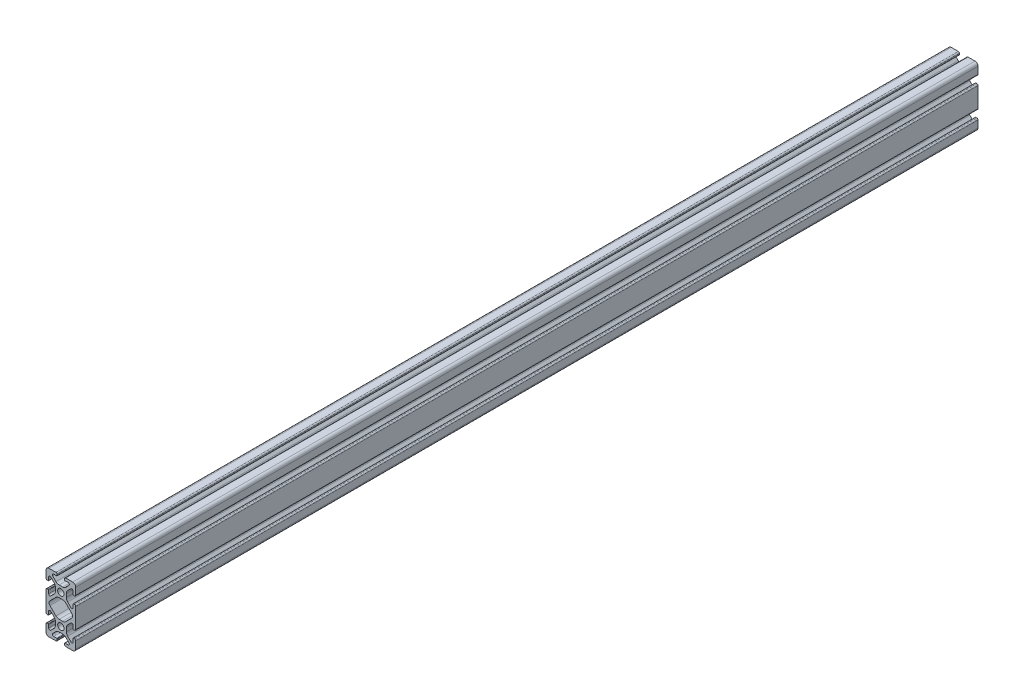
SolidWorks part; units mm, degrees
ref_plane "Front Plane" through (0, 0, 0) normal (0, 0, 1) x (1, 0, 0)
ref_plane "Top Plane" through (0, 0, 0) normal (0, 1, 0) x (1, 0, 0)
ref_plane "Right Plane" through (0, 0, 0) normal (1, 0, 0) x (0, 0, -1)
sketch "Sketch1" plane through (0, 0, 0) normal (0, 0, 1) x (1, 0, 0)
  line L0 (0, 10) -> (0, 20) construction
  line L1 (0, 10) -> (10, 10) construction
  line L2 (0, 10) -> (-10, 20) construction
  line L3 (-8, 20) -> (-3.3, 20)
  line L4 (-10, 20) -> (0, 20) construction
  line L6 (-2.8, 18.2) -> (-4.9051, 18.2)
  line L10 (0, 13.7) -> (-1.2022, 13.7)
  line L11 (-3.3236, 14.5787) -> (-5.5025, 16.7576)
  line L24 (0, 10) -> (-10, 10) construction
  line L25 (-10, 10) -> (0, 10) construction
  line L27 (-10, 0) -> (-10, 20) construction
  line L28 (0, 20) -> (10, 20) construction
  line L29 (-2.5, 18.5) -> (-2.5, 19.2)
  line L30 (-10, -20) -> (10, -20) construction
  line L31 (0, 20) -> (0, -20) construction
  arc A0 (-9.4142, 19.4142) -> (-8, 20) centre (-8, 18) cw
  arc A5 (-3.3, 20) -> (-2.5, 19.2) centre (-3.3, 19.2) cw
  arc A6 (-1.2022, 13.7) -> (-3.3236, 14.5787) centre (-1.2022, 16.7) cw
  circle A16 centre (0, 10) radius 2.15
  arc A18 (-5.5025, 16.7576) -> (-4.9051, 18.2) centre (-4.9051, 17.3551) cw
  arc A20 (-2.8, 18.2) -> (-2.5, 18.5) centre (-2.8, 18.5) ccw
  point P15 (0, -20)
  point P24 (0, 0)
  point P42 (-2.4449, 13.7)
  point P80 (-10, 10)
  dimension "D11" = 2
  dimension "D15" = 3
  dimension "Center Hole Diameter" = 4.3
  dimension "D7" = 0.8
  dimension "D8" = 0.3
  dimension "D4" = 0.8449
  dimension "D1" = 45
  dimension "Rail Width" = 20
  dimension "T-Slot Depth" = 6.3
  dimension "D9" = 1.8
  dimension "D23" = 7.4
  dimension "D5" = 11.5
  dimension "T-Slot Width" = 5
  dimension "D3" = 1.775
  dimension "D6" = 9.8102
  dimension "Rail Height" = 40
sketch "Sketch2" plane through (0, 0, 0) normal (1, 0, 0) x (0, 0, -1)
  line L0 (-304.8, 0) -> (304.8, 0)
  line L1 (-304.8, -20) -> (-304.8, 20)
  line L2 (0, 10) -> (0, 20) construction
  line L3 (0, 0) -> (0, 20) construction
  line L4 (304.8, -20) -> (304.8, 20)
  line L5 (-10, 10) -> (10, 10) construction
  point P0 (-279.8, 0)
  point P3 (0, 0)
  point P7 (279.8, 0)
  point P11 (-304.8, 0)
  point P14 (304.8, 0)
  point P23 (0, 10)
  dimension "D1" = 25
  dimension "Length" = 609.6
sketch "Sketch3" plane through (0, 0, 0) normal (0, 0, 1) x (1, 0, 0)
  line L0 (-2.5, 18.5) -> (-2.5, 19.2) construction
  line L1 (0, 10) -> (-10, 20) construction
  line L2 (0, 10) -> (-10, 20) construction
  line L5 (-8, 20) -> (-3.3, 20) construction
  line L6 (-2.8, 18.2) -> (-4.9051, 18.2) construction
  line L7 (-8.5, 7.5) -> (-9.2, 7.5)
  line L17 (-2.5, 18.5) -> (-2.5, 19.2)
  line L19 (-2.8, 18.2) -> (-4.9051, 18.2)
  line L21 (-3.7, 10) -> (0, 10) construction
  line L22 (-3.7, 8.7978) -> (-3.7, 11.2022)
  line L23 (-4.5787, 13.3236) -> (-6.7576, 15.5025)
  line L42 (-3.3236, 14.5787) -> (-5.5025, 16.7576) construction
  line L43 (0, 13.7) -> (-1.2022, 13.7) construction
  line L44 (-8, 20) -> (-3.3, 20)
  line L47 (-3.3236, 14.5787) -> (-5.5025, 16.7576)
  line L48 (1.2022, 13.7) -> (-1.2022, 13.7)
  line L59 (0, 13.7) -> (0, 12.15) construction
  line L60 (-10, 18) -> (-10, 13.3)
  line L61 (-8.2, 12.8) -> (-8.2, 14.9051)
  line L62 (-8.5, 12.5) -> (-9.2, 12.5)
  line L63 (-8.2, 7.2) -> (-8.2, 5.0949)
  line L64 (-10, 0) -> (-10, 6.7)
  line L65 (1.2022, 6.3) -> (-1.2022, 6.3)
  line L66 (-3.3236, 5.4213) -> (-7.3307, 1.4142)
  line L68 (-4.5787, 6.6764) -> (-6.7576, 4.4975)
  line L73 (10, 0) -> (-10, 0) construction
  line L78 (4.5787, 6.6764) -> (6.7576, 4.4975)
  line L79 (3.3236, 5.4213) -> (7.3307, 1.4142)
  line L81 (10, 0) -> (10, 6.7)
  line L82 (8.2, 7.2) -> (8.2, 5.0949)
  line L83 (8.5, 12.5) -> (9.2, 12.5)
  line L84 (8.2, 12.8) -> (8.2, 14.9051)
  line L85 (10, 18) -> (10, 13.3)
  line L87 (3.3236, 14.5787) -> (5.5025, 16.7576)
  line L88 (8, 20) -> (3.3, 20)
  line L89 (4.5787, 13.3236) -> (6.7576, 15.5025)
  line L90 (3.7, 8.7978) -> (3.7, 11.2022)
  line L91 (2.8, 18.2) -> (4.9051, 18.2)
  line L92 (2.5, 18.5) -> (2.5, 19.2)
  line L93 (8.5, 7.5) -> (9.2, 7.5)
  line L94 (-10, 0) -> (-7.9165, 0)
  line L96 (7.9165, 0) -> (10, 0)
  arc A0 (-8, 20) -> (-9.4142, 19.4142) centre (-8, 18) ccw construction
  arc A1 (-2.8, 18.2) -> (-2.5, 18.5) centre (-2.8, 18.5) ccw construction
  arc A3 (-2.8, 18.2) -> (-2.5, 18.5) centre (-2.8, 18.5) ccw
  arc A5 (-8, 20) -> (-10, 18) centre (-8, 18) ccw
  arc A10 (-3.3236, 5.4213) -> (-1.2022, 6.3) centre (-1.2022, 3.3) cw
  circle A13 centre (0, 10) radius 2.15 construction
  circle A14 centre (0, 10) radius 2.15
  arc A15 (-4.5787, 13.3236) -> (-3.7, 11.2022) centre (-6.7, 11.2022) cw
  arc A16 (-8.2, 14.9051) -> (-6.7576, 15.5025) centre (-7.3551, 14.9051) cw
  arc A17 (-9.2, 12.5) -> (-10, 13.3) centre (-9.2, 13.3) cw
  arc A18 (-8.2, 12.8) -> (-8.5, 12.5) centre (-8.5, 12.8) cw
  arc A36 (-2.5, 19.2) -> (-3.3, 20) centre (-3.3, 19.2) ccw construction
  arc A38 (-4.9051, 18.2) -> (-5.5025, 16.7576) centre (-4.9051, 17.3551) ccw construction
  arc A39 (-3.3236, 14.5787) -> (-1.2022, 13.7) centre (-1.2022, 16.7) ccw construction
  arc A41 (-2.5, 19.2) -> (-3.3, 20) centre (-3.3, 19.2) ccw
  arc A43 (-4.9051, 18.2) -> (-5.5025, 16.7576) centre (-4.9051, 17.3551) ccw
  arc A44 (-3.3236, 14.5787) -> (-1.2022, 13.7) centre (-1.2022, 16.7) ccw
  arc A47 (-8.2, 7.2) -> (-8.5, 7.5) centre (-8.5, 7.2) ccw
  arc A48 (-9.2, 7.5) -> (-10, 6.7) centre (-9.2, 6.7) ccw
  arc A49 (-8.2, 5.0949) -> (-6.7576, 4.4975) centre (-7.3551, 5.0949) ccw
  arc A50 (-4.5787, 6.6764) -> (-3.7, 8.7978) centre (-6.7, 8.7978) ccw
  arc A54 (-7.9165, 0) -> (-7.3307, 1.4142) centre (-5.9165, 0) cw
  arc A57 (7.9165, 0) -> (7.3307, 1.4142) centre (5.9165, 0) ccw
  arc A58 (4.5787, 6.6764) -> (3.7, 8.7978) centre (6.7, 8.7978) cw
  arc A59 (8.2, 5.0949) -> (6.7576, 4.4975) centre (7.3551, 5.0949) cw
  arc A60 (9.2, 7.5) -> (10, 6.7) centre (9.2, 6.7) cw
  arc A61 (8.2, 7.2) -> (8.5, 7.5) centre (8.5, 7.2) cw
  arc A62 (3.3236, 14.5787) -> (1.2022, 13.7) centre (1.2022, 16.7) cw
  arc A63 (4.9051, 18.2) -> (5.5025, 16.7576) centre (4.9051, 17.3551) cw
  arc A64 (2.5, 19.2) -> (3.3, 20) centre (3.3, 19.2) cw
  arc A65 (8.2, 12.8) -> (8.5, 12.5) centre (8.5, 12.8) ccw
  arc A66 (9.2, 12.5) -> (10, 13.3) centre (9.2, 13.3) ccw
  arc A67 (8.2, 14.9051) -> (6.7576, 15.5025) centre (7.3551, 14.9051) ccw
  arc A68 (4.5787, 13.3236) -> (3.7, 11.2022) centre (6.7, 11.2022) ccw
  arc A70 (3.3236, 5.4213) -> (1.2022, 6.3) centre (1.2022, 3.3) ccw
  arc A71 (8, 20) -> (10, 18) centre (8, 18) cw
  arc A72 (2.8, 18.2) -> (2.5, 18.5) centre (2.8, 18.5) cw
  point P59 (-10, 2)
  point P71 (0, 0)
  point P116 (0, 6.3)
extrude "Boss-Extrude1" add sketch "Sketch3" along normal mid plane 609.6
pattern_circular "CirPattern1" count 2 over 360 about axis through (0, 0, 0) along (0, 0, 1) of "Boss-Extrude1"
sketch "Sketch4" plane through (0, 0, 304.8) normal (0, 0, 1) x (1, 0, 0)
  line L0 (7.3307, -1.4142) -> (3.3236, -5.4213) construction
  line L1 (-3.3236, -5.4213) -> (-7.3307, -1.4142) construction
  line L2 (1.2022, -6.3) -> (-1.2022, -6.3) construction
  line L3 (3.3236, 5.4213) -> (7.3307, 1.4142) construction
  line L4 (-1.2022, 6.3) -> (1.2022, 6.3) construction
  line L5 (-7.3307, 1.4142) -> (-3.3236, 5.4213) construction
  line L6 (7.3307, -1.4142) -> (3.3236, -5.4213)
  line L7 (-3.3236, -5.4213) -> (-7.3307, -1.4142)
  line L8 (1.2022, -6.3) -> (-1.2022, -6.3)
  line L9 (3.3236, 5.4213) -> (7.3307, 1.4142)
  line L10 (-1.2022, 6.3) -> (1.2022, 6.3)
  line L11 (-7.3307, 1.4142) -> (-3.3236, 5.4213)
  line L52 (-2.5, 18.5) -> (-2.5, 19.2)
  line L53 (-3.3, 20) -> (-8, 20)
  line L54 (-10, 18) -> (-10, 13.3)
  line L55 (-9.2, 12.5) -> (-8.5, 12.5)
  line L56 (-8.2, 12.8) -> (-8.2, 14.9051)
  line L57 (-6.7576, 15.5025) -> (-4.5787, 13.3236)
  line L58 (-3.7, 11.2022) -> (-3.7, 8.7978)
  line L59 (-4.5787, 6.6764) -> (-6.7576, 4.4975)
  line L60 (-8.2, 5.0949) -> (-8.2, 7.2)
  line L61 (-8.5, 7.5) -> (-9.2, 7.5)
  line L62 (-10, 6.7) -> (-10, -6.7)
  line L63 (-9.2, -7.5) -> (-8.5, -7.5)
  line L64 (-8.2, -7.2) -> (-8.2, -5.0949)
  line L65 (-6.7576, -4.4975) -> (-4.5787, -6.6764)
  line L66 (-3.7, -8.7978) -> (-3.7, -11.2022)
  line L67 (-4.5787, -13.3236) -> (-6.7576, -15.5025)
  line L68 (-8.2, -14.9051) -> (-8.2, -12.8)
  line L69 (-8.5, -12.5) -> (-9.2, -12.5)
  line L70 (-10, -13.3) -> (-10, -18)
  line L71 (-8, -20) -> (-3.3, -20)
  line L72 (-2.5, -19.2) -> (-2.5, -18.5)
  line L73 (-2.8, -18.2) -> (-4.9051, -18.2)
  line L74 (-5.5025, -16.7576) -> (-3.3236, -14.5787)
  line L75 (-1.2022, -13.7) -> (1.2022, -13.7)
  line L76 (3.3236, -14.5787) -> (5.5025, -16.7576)
  line L77 (4.9051, -18.2) -> (2.8, -18.2)
  line L78 (2.5, -18.5) -> (2.5, -19.2)
  line L79 (3.3, -20) -> (8, -20)
  line L80 (10, -18) -> (10, -13.3)
  line L81 (9.2, -12.5) -> (8.5, -12.5)
  line L82 (8.2, -12.8) -> (8.2, -14.9051)
  line L83 (6.7576, -15.5025) -> (4.5787, -13.3236)
  line L84 (3.7, -11.2022) -> (3.7, -8.7978)
  line L85 (4.5787, -6.6764) -> (6.7576, -4.4975)
  line L86 (8.2, -5.0949) -> (8.2, -7.2)
  line L87 (8.5, -7.5) -> (9.2, -7.5)
  line L88 (10, -6.7) -> (10, 6.7)
  line L89 (9.2, 7.5) -> (8.5, 7.5)
  line L90 (8.2, 7.2) -> (8.2, 5.0949)
  line L91 (6.7576, 4.4975) -> (4.5787, 6.6764)
  line L92 (3.7, 8.7978) -> (3.7, 11.2022)
  line L93 (4.5787, 13.3236) -> (6.7576, 15.5025)
  line L94 (8.2, 14.9051) -> (8.2, 12.8)
  line L95 (8.5, 12.5) -> (9.2, 12.5)
  line L96 (10, 13.3) -> (10, 18)
  line L97 (8, 20) -> (3.3, 20)
  line L98 (2.5, 19.2) -> (2.5, 18.5)
  line L99 (2.8, 18.2) -> (4.9051, 18.2)
  line L100 (5.5025, 16.7576) -> (3.3236, 14.5787)
  line L101 (1.2022, 13.7) -> (-1.2022, 13.7)
  line L102 (-3.3236, 14.5787) -> (-5.5025, 16.7576)
  line L103 (-4.9051, 18.2) -> (-2.8, 18.2)
  line L104 (-2.5, 18.5) -> (-2.5, 19.2)
  line L105 (-3.3, 20) -> (-8, 20)
  line L106 (-10, 18) -> (-10, 13.3)
  line L107 (-9.2, 12.5) -> (-8.5, 12.5)
  line L108 (-8.2, 12.8) -> (-8.2, 14.9051)
  line L109 (-6.7576, 15.5025) -> (-4.5787, 13.3236)
  line L110 (-3.7, 11.2022) -> (-3.7, 8.7978)
  line L111 (-4.5787, 6.6764) -> (-6.7576, 4.4975)
  line L112 (-8.2, 5.0949) -> (-8.2, 7.2)
  line L113 (-8.5, 7.5) -> (-9.2, 7.5)
  line L114 (-10, 6.7) -> (-10, -6.7)
  line L115 (-9.2, -7.5) -> (-8.5, -7.5)
  line L116 (-8.2, -7.2) -> (-8.2, -5.0949)
  line L117 (-6.7576, -4.4975) -> (-4.5787, -6.6764)
  line L118 (-3.7, -8.7978) -> (-3.7, -11.2022)
  line L119 (-4.5787, -13.3236) -> (-6.7576, -15.5025)
  line L120 (-8.2, -14.9051) -> (-8.2, -12.8)
  line L121 (-8.5, -12.5) -> (-9.2, -12.5)
  line L122 (-10, -13.3) -> (-10, -18)
  line L123 (-8, -20) -> (-3.3, -20)
  line L124 (-2.5, -19.2) -> (-2.5, -18.5)
  line L125 (-2.8, -18.2) -> (-4.9051, -18.2)
  line L126 (-5.5025, -16.7576) -> (-3.3236, -14.5787)
  line L127 (-1.2022, -13.7) -> (1.2022, -13.7)
  line L128 (3.3236, -14.5787) -> (5.5025, -16.7576)
  line L129 (4.9051, -18.2) -> (2.8, -18.2)
  line L130 (2.5, -18.5) -> (2.5, -19.2)
  line L131 (3.3, -20) -> (8, -20)
  line L132 (10, -18) -> (10, -13.3)
  line L133 (9.2, -12.5) -> (8.5, -12.5)
  line L134 (8.2, -12.8) -> (8.2, -14.9051)
  line L135 (6.7576, -15.5025) -> (4.5787, -13.3236)
  line L136 (3.7, -11.2022) -> (3.7, -8.7978)
  line L137 (4.5787, -6.6764) -> (6.7576, -4.4975)
  line L138 (8.2, -5.0949) -> (8.2, -7.2)
  line L139 (8.5, -7.5) -> (9.2, -7.5)
  line L140 (10, -6.7) -> (10, 6.7)
  line L141 (9.2, 7.5) -> (8.5, 7.5)
  line L142 (8.2, 7.2) -> (8.2, 5.0949)
  line L143 (6.7576, 4.4975) -> (4.5787, 6.6764)
  line L144 (3.7, 8.7978) -> (3.7, 11.2022)
  line L145 (4.5787, 13.3236) -> (6.7576, 15.5025)
  line L146 (8.2, 14.9051) -> (8.2, 12.8)
  line L147 (8.5, 12.5) -> (9.2, 12.5)
  line L148 (10, 13.3) -> (10, 18)
  line L149 (8, 20) -> (3.3, 20)
  line L150 (2.5, 19.2) -> (2.5, 18.5)
  line L151 (2.8, 18.2) -> (4.9051, 18.2)
  line L152 (5.5025, 16.7576) -> (3.3236, 14.5787)
  line L153 (1.2022, 13.7) -> (-1.2022, 13.7)
  line L154 (-3.3236, 14.5787) -> (-5.5025, 16.7576)
  line L155 (-4.9051, 18.2) -> (-2.8, 18.2)
  circle A0 centre (0, 10) radius 2.15 construction
  arc A1 (-7.3307, 1.4142) -> (-7.3307, -1.4142) centre (-5.9165, 0) ccw construction
  arc A2 (-3.3236, -5.4213) -> (-1.2022, -6.3) centre (-1.2022, -3.3) ccw construction
  arc A3 (1.2022, -6.3) -> (3.3236, -5.4213) centre (1.2022, -3.3) ccw construction
  circle A4 centre (0, -10) radius 2.15 construction
  arc A5 (7.3307, -1.4142) -> (7.3307, 1.4142) centre (5.9165, 0) ccw construction
  arc A6 (3.3236, 5.4213) -> (1.2022, 6.3) centre (1.2022, 3.3) ccw construction
  arc A7 (-1.2022, 6.3) -> (-3.3236, 5.4213) centre (-1.2022, 3.3) ccw construction
  circle A8 centre (0, 10) radius 2.15
  arc A9 (-7.3307, 1.4142) -> (-7.3307, -1.4142) centre (-5.9165, 0) ccw
  arc A10 (-3.3236, -5.4213) -> (-1.2022, -6.3) centre (-1.2022, -3.3) ccw
  arc A11 (1.2022, -6.3) -> (3.3236, -5.4213) centre (1.2022, -3.3) ccw
  circle A12 centre (0, -10) radius 2.15
  arc A13 (7.3307, -1.4142) -> (7.3307, 1.4142) centre (5.9165, 0) ccw
  arc A14 (3.3236, 5.4213) -> (1.2022, 6.3) centre (1.2022, 3.3) ccw
  arc A15 (-1.2022, 6.3) -> (-3.3236, 5.4213) centre (-1.2022, 3.3) ccw
  arc A52 (-2.8, 18.2) -> (-2.5, 18.5) centre (-2.8, 18.5) ccw
  arc A53 (-2.5, 19.2) -> (-3.3, 20) centre (-3.3, 19.2) ccw
  arc A54 (-8, 20) -> (-10, 18) centre (-8, 18) ccw
  arc A55 (-10, 13.3) -> (-9.2, 12.5) centre (-9.2, 13.3) ccw
  arc A56 (-8.5, 12.5) -> (-8.2, 12.8) centre (-8.5, 12.8) ccw
  arc A57 (-6.7576, 15.5025) -> (-8.2, 14.9051) centre (-7.3551, 14.9051) ccw
  arc A58 (-3.7, 11.2022) -> (-4.5787, 13.3236) centre (-6.7, 11.2022) ccw
  arc A59 (-4.5787, 6.6764) -> (-3.7, 8.7978) centre (-6.7, 8.7978) ccw
  arc A60 (-8.2, 5.0949) -> (-6.7576, 4.4975) centre (-7.3551, 5.0949) ccw
  arc A61 (-8.2, 7.2) -> (-8.5, 7.5) centre (-8.5, 7.2) ccw
  arc A62 (-9.2, 7.5) -> (-10, 6.7) centre (-9.2, 6.7) ccw
  arc A63 (-10, -6.7) -> (-9.2, -7.5) centre (-9.2, -6.7) ccw
  arc A64 (-8.5, -7.5) -> (-8.2, -7.2) centre (-8.5, -7.2) ccw
  arc A65 (-6.7576, -4.4975) -> (-8.2, -5.0949) centre (-7.3551, -5.0949) ccw
  arc A66 (-3.7, -8.7978) -> (-4.5787, -6.6764) centre (-6.7, -8.7978) ccw
  arc A67 (-4.5787, -13.3236) -> (-3.7, -11.2022) centre (-6.7, -11.2022) ccw
  arc A68 (-8.2, -14.9051) -> (-6.7576, -15.5025) centre (-7.3551, -14.9051) ccw
  arc A69 (-8.2, -12.8) -> (-8.5, -12.5) centre (-8.5, -12.8) ccw
  arc A70 (-9.2, -12.5) -> (-10, -13.3) centre (-9.2, -13.3) ccw
  arc A71 (-10, -18) -> (-8, -20) centre (-8, -18) ccw
  arc A72 (-3.3, -20) -> (-2.5, -19.2) centre (-3.3, -19.2) ccw
  arc A73 (-2.5, -18.5) -> (-2.8, -18.2) centre (-2.8, -18.5) ccw
  arc A74 (-5.5025, -16.7576) -> (-4.9051, -18.2) centre (-4.9051, -17.3551) ccw
  arc A75 (-1.2022, -13.7) -> (-3.3236, -14.5787) centre (-1.2022, -16.7) ccw
  arc A76 (3.3236, -14.5787) -> (1.2022, -13.7) centre (1.2022, -16.7) ccw
  arc A77 (4.9051, -18.2) -> (5.5025, -16.7576) centre (4.9051, -17.3551) ccw
  arc A78 (2.8, -18.2) -> (2.5, -18.5) centre (2.8, -18.5) ccw
  arc A79 (2.5, -19.2) -> (3.3, -20) centre (3.3, -19.2) ccw
  arc A80 (8, -20) -> (10, -18) centre (8, -18) ccw
  arc A81 (10, -13.3) -> (9.2, -12.5) centre (9.2, -13.3) ccw
  arc A82 (8.5, -12.5) -> (8.2, -12.8) centre (8.5, -12.8) ccw
  arc A83 (6.7576, -15.5025) -> (8.2, -14.9051) centre (7.3551, -14.9051) ccw
  arc A84 (3.7, -11.2022) -> (4.5787, -13.3236) centre (6.7, -11.2022) ccw
  arc A85 (4.5787, -6.6764) -> (3.7, -8.7978) centre (6.7, -8.7978) ccw
  arc A86 (8.2, -5.0949) -> (6.7576, -4.4975) centre (7.3551, -5.0949) ccw
  arc A87 (8.2, -7.2) -> (8.5, -7.5) centre (8.5, -7.2) ccw
  arc A88 (9.2, -7.5) -> (10, -6.7) centre (9.2, -6.7) ccw
  arc A89 (10, 6.7) -> (9.2, 7.5) centre (9.2, 6.7) ccw
  arc A90 (8.5, 7.5) -> (8.2, 7.2) centre (8.5, 7.2) ccw
  arc A91 (6.7576, 4.4975) -> (8.2, 5.0949) centre (7.3551, 5.0949) ccw
  arc A92 (3.7, 8.7978) -> (4.5787, 6.6764) centre (6.7, 8.7978) ccw
  arc A93 (4.5787, 13.3236) -> (3.7, 11.2022) centre (6.7, 11.2022) ccw
  arc A94 (8.2, 14.9051) -> (6.7576, 15.5025) centre (7.3551, 14.9051) ccw
  arc A95 (8.2, 12.8) -> (8.5, 12.5) centre (8.5, 12.8) ccw
  arc A96 (9.2, 12.5) -> (10, 13.3) centre (9.2, 13.3) ccw
  arc A97 (10, 18) -> (8, 20) centre (8, 18) ccw
  arc A98 (3.3, 20) -> (2.5, 19.2) centre (3.3, 19.2) ccw
  arc A99 (2.5, 18.5) -> (2.8, 18.2) centre (2.8, 18.5) ccw
  arc A100 (5.5025, 16.7576) -> (4.9051, 18.2) centre (4.9051, 17.3551) ccw
  arc A101 (1.2022, 13.7) -> (3.3236, 14.5787) centre (1.2022, 16.7) ccw
  arc A102 (-3.3236, 14.5787) -> (-1.2022, 13.7) centre (-1.2022, 16.7) ccw
  arc A103 (-4.9051, 18.2) -> (-5.5025, 16.7576) centre (-4.9051, 17.3551) ccw
  arc A104 (-2.8, 18.2) -> (-2.5, 18.5) centre (-2.8, 18.5) ccw
  arc A105 (-2.5, 19.2) -> (-3.3, 20) centre (-3.3, 19.2) ccw
  arc A106 (-8, 20) -> (-10, 18) centre (-8, 18) ccw
  arc A107 (-10, 13.3) -> (-9.2, 12.5) centre (-9.2, 13.3) ccw
  arc A108 (-8.5, 12.5) -> (-8.2, 12.8) centre (-8.5, 12.8) ccw
  arc A109 (-6.7576, 15.5025) -> (-8.2, 14.9051) centre (-7.3551, 14.9051) ccw
  arc A110 (-3.7, 11.2022) -> (-4.5787, 13.3236) centre (-6.7, 11.2022) ccw
  arc A111 (-4.5787, 6.6764) -> (-3.7, 8.7978) centre (-6.7, 8.7978) ccw
  arc A112 (-8.2, 5.0949) -> (-6.7576, 4.4975) centre (-7.3551, 5.0949) ccw
  arc A113 (-8.2, 7.2) -> (-8.5, 7.5) centre (-8.5, 7.2) ccw
  arc A114 (-9.2, 7.5) -> (-10, 6.7) centre (-9.2, 6.7) ccw
  arc A115 (-10, -6.7) -> (-9.2, -7.5) centre (-9.2, -6.7) ccw
  arc A116 (-8.5, -7.5) -> (-8.2, -7.2) centre (-8.5, -7.2) ccw
  arc A117 (-6.7576, -4.4975) -> (-8.2, -5.0949) centre (-7.3551, -5.0949) ccw
  arc A118 (-3.7, -8.7978) -> (-4.5787, -6.6764) centre (-6.7, -8.7978) ccw
  arc A119 (-4.5787, -13.3236) -> (-3.7, -11.2022) centre (-6.7, -11.2022) ccw
  arc A120 (-8.2, -14.9051) -> (-6.7576, -15.5025) centre (-7.3551, -14.9051) ccw
  arc A121 (-8.2, -12.8) -> (-8.5, -12.5) centre (-8.5, -12.8) ccw
  arc A122 (-9.2, -12.5) -> (-10, -13.3) centre (-9.2, -13.3) ccw
  arc A123 (-10, -18) -> (-8, -20) centre (-8, -18) ccw
  arc A124 (-3.3, -20) -> (-2.5, -19.2) centre (-3.3, -19.2) ccw
  arc A125 (-2.5, -18.5) -> (-2.8, -18.2) centre (-2.8, -18.5) ccw
  arc A126 (-5.5025, -16.7576) -> (-4.9051, -18.2) centre (-4.9051, -17.3551) ccw
  arc A127 (-1.2022, -13.7) -> (-3.3236, -14.5787) centre (-1.2022, -16.7) ccw
  arc A128 (3.3236, -14.5787) -> (1.2022, -13.7) centre (1.2022, -16.7) ccw
  arc A129 (4.9051, -18.2) -> (5.5025, -16.7576) centre (4.9051, -17.3551) ccw
  arc A130 (2.8, -18.2) -> (2.5, -18.5) centre (2.8, -18.5) ccw
  arc A131 (2.5, -19.2) -> (3.3, -20) centre (3.3, -19.2) ccw
  arc A132 (8, -20) -> (10, -18) centre (8, -18) ccw
  arc A133 (10, -13.3) -> (9.2, -12.5) centre (9.2, -13.3) ccw
  arc A134 (8.5, -12.5) -> (8.2, -12.8) centre (8.5, -12.8) ccw
  arc A135 (6.7576, -15.5025) -> (8.2, -14.9051) centre (7.3551, -14.9051) ccw
  arc A136 (3.7, -11.2022) -> (4.5787, -13.3236) centre (6.7, -11.2022) ccw
  arc A137 (4.5787, -6.6764) -> (3.7, -8.7978) centre (6.7, -8.7978) ccw
  arc A138 (8.2, -5.0949) -> (6.7576, -4.4975) centre (7.3551, -5.0949) ccw
  arc A139 (8.2, -7.2) -> (8.5, -7.5) centre (8.5, -7.2) ccw
  arc A140 (9.2, -7.5) -> (10, -6.7) centre (9.2, -6.7) ccw
  arc A141 (10, 6.7) -> (9.2, 7.5) centre (9.2, 6.7) ccw
  arc A142 (8.5, 7.5) -> (8.2, 7.2) centre (8.5, 7.2) ccw
  arc A143 (6.7576, 4.4975) -> (8.2, 5.0949) centre (7.3551, 5.0949) ccw
  arc A144 (3.7, 8.7978) -> (4.5787, 6.6764) centre (6.7, 8.7978) ccw
  arc A145 (4.5787, 13.3236) -> (3.7, 11.2022) centre (6.7, 11.2022) ccw
  arc A146 (8.2, 14.9051) -> (6.7576, 15.5025) centre (7.3551, 14.9051) ccw
  arc A147 (8.2, 12.8) -> (8.5, 12.5) centre (8.5, 12.8) ccw
  arc A148 (9.2, 12.5) -> (10, 13.3) centre (9.2, 13.3) ccw
  arc A149 (10, 18) -> (8, 20) centre (8, 18) ccw
  arc A150 (3.3, 20) -> (2.5, 19.2) centre (3.3, 19.2) ccw
  arc A151 (2.5, 18.5) -> (2.8, 18.2) centre (2.8, 18.5) ccw
  arc A152 (5.5025, 16.7576) -> (4.9051, 18.2) centre (4.9051, 17.3551) ccw
  arc A153 (1.2022, 13.7) -> (3.3236, 14.5787) centre (1.2022, 16.7) ccw
  arc A154 (-3.3236, 14.5787) -> (-1.2022, 13.7) centre (-1.2022, 16.7) ccw
  arc A155 (-4.9051, 18.2) -> (-5.5025, 16.7576) centre (-4.9051, 17.3551) ccw
  dimension "D1" = 0
extrude "Cut-Extrude1" cut sketch "Sketch4" against normal blind 2.09
equation "\"D1@Sketch2\"=\"Rail Width@Sketch1\"*1.25"
equation "\"D1@Boss-Extrude1\" = \"Length@Sketch2\""
